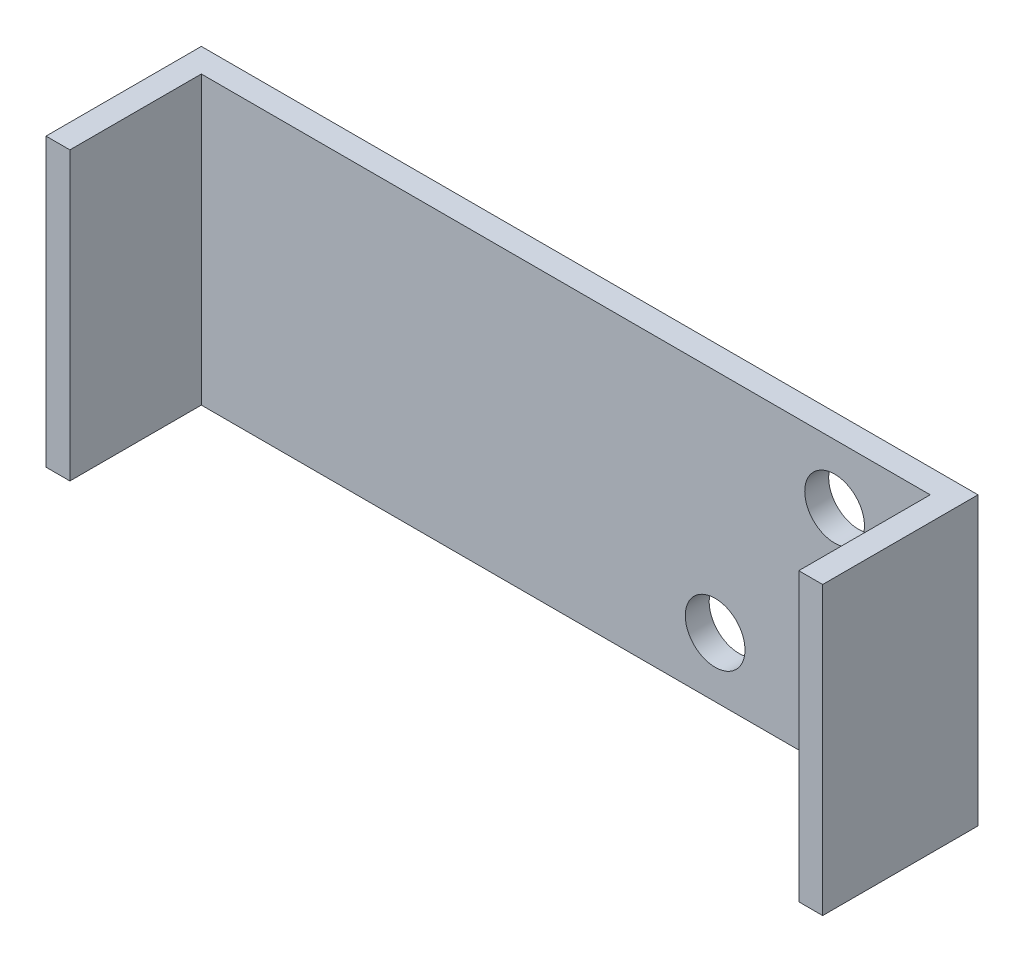
SolidWorks part; units mm, degrees
ref_plane "前基準面" through (0, 0, 0) normal (0, 0, 1) x (1, 0, 0)
ref_plane "上基準面" through (0, 0, 0) normal (0, 1, 0) x (1, 0, 0)
ref_plane "右基準面" through (0, 0, 0) normal (1, 0, 0) x (0, 0, -1)
sketch "草圖1" plane through (0, 0, 0) normal (0, 0, 1) x (1, 0, 0)
  line L1 (0, 0) -> (-65, 0)
  line L2 (0, 0) -> (0, 24)
  line L3 (0, 24) -> (-65, 24)
  line L4 (-65, 0) -> (-65, 24)
  dimension "D1" = 65
  dimension "D2" = 24
extrude "填料-伸長1" add sketch "草圖1" along normal blind 13
sketch "草圖2" plane through (0, 0, 13) normal (0, 0, 1) x (1, 0, 0)
  line L0 (-65, 0) -> (0, 0) construction
  line L1 (-63, 24) -> (-2, 24)
  line L2 (-63, 24) -> (-63, 0)
  line L3 (-63, 0) -> (-2, 0)
  line L4 (-2, 24) -> (-2, 0)
  line L5 (-65, 24) -> (-65, 0) construction
  dimension "D1" = 24
  dimension "D2" = 0
  dimension "D3" = 61
  dimension "D4" = 2
extrude "除料-伸長1" cut sketch "草圖2" against normal blind 11
sketch "草圖14" plane through (0, 0, 0) normal (0, 0, -1) x (-1, 0, 0)
  line L1 (0, 0) -> (0, 24) construction
  line L2 (0, 24) -> (65, 24) construction
  circle A0 centre (10, 19) radius 2.5
  circle A1 centre (20, 5) radius 2.5
  point P10 (0, 0)
  dimension "D2" = 5
  dimension "D3" = 5
  dimension "D6" = 5
  dimension "D1" = 10
  dimension "D4" = 20
  dimension "D5" = 19
extrude "除料-伸長2" cut sketch "草圖14" against normal blind 2
